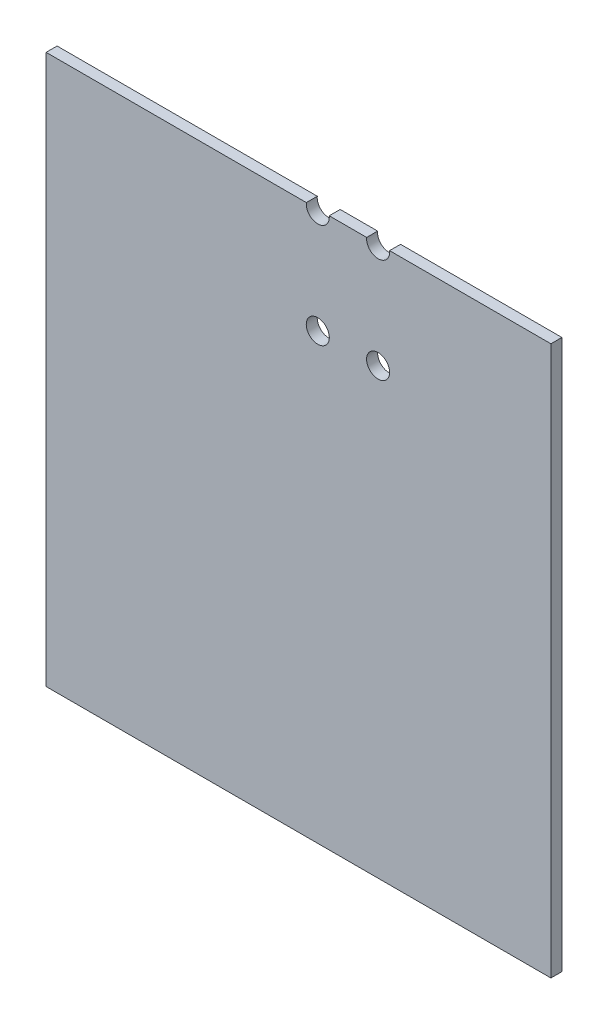
SolidWorks part; units mm, degrees
ref_plane "Piano frontale" through (0, 0, 0) normal (0, 0, 1) x (1, 0, 0)
ref_plane "Piano superiore" through (0, 0, 0) normal (0, 1, 0) x (1, 0, 0)
ref_plane "Piano destro" through (0, 0, 0) normal (1, 0, 0) x (0, 0, -1)
sketch "Schizzo1" plane through (0, 0, 218.1033) normal (0, 0, 1) x (1, 0, 0)
  line L1 (154.879, -270.5203) -> (-29.121, -270.5203)
  line L2 (154.879, -270.5203) -> (154.879, -70.3032)
  line L3 (154.879, -70.3032) -> (-29.121, -70.3032)
  line L4 (-29.121, -270.5203) -> (-29.121, -70.3032)
  line L6 (167.8978, -89.7524) -> (167.8978, -75.7524) construction
  line L7 (167.8978, -89.7524) -> (167.8978, -75.7524) construction
  line L8 (-16.1022, -143.7524) -> (-16.1022, -129.7524) construction
  line L9 (-16.1022, -143.7524) -> (-16.1022, -129.7524) construction
  line L11 (98.0978, -65.7524) -> (63.6978, -65.7524) construction
  line L12 (98.0978, -65.7524) -> (63.6978, -65.7524) construction
extrude "Estrusione-Estrusione1" add sketch "Schizzo1" along normal blind 4 contours L3 L4 L1 L2
hole_wizard "M8 Clearance Hole2" positions "Sketch9" profile "Sketch8" hole size "M8" standard "ISO" end condition through all
sketch "Sketch9" plane through (0, 0, 218.1033) normal (0, 0, 1) x (1, 0, 0)
  point P0 (91.8978, -70.7524)
  point P3 (69.8978, -70.7524)
  point P6 (91.8978, -108.7524)
  point P9 (69.8978, -108.7524)
sketch "Sketch8" plane through (91.8978, -70.7524, 218.1033) normal (1, 0, 0) x (0, 1, 0)
  line L0 (0, 0) -> (0, 4)
  line L1 (0, 4) -> (4.2, 4)
  line L2 (4.2, 4) -> (4.2, 0)
  line L5 (4.2, 0) -> (0, 0)
  line L11 (0, -6.35) -> (0, 107.95) construction
  dimension "Thru Hole Dia." = 8.4
  dimension "Thru Hole Depth" = 4
